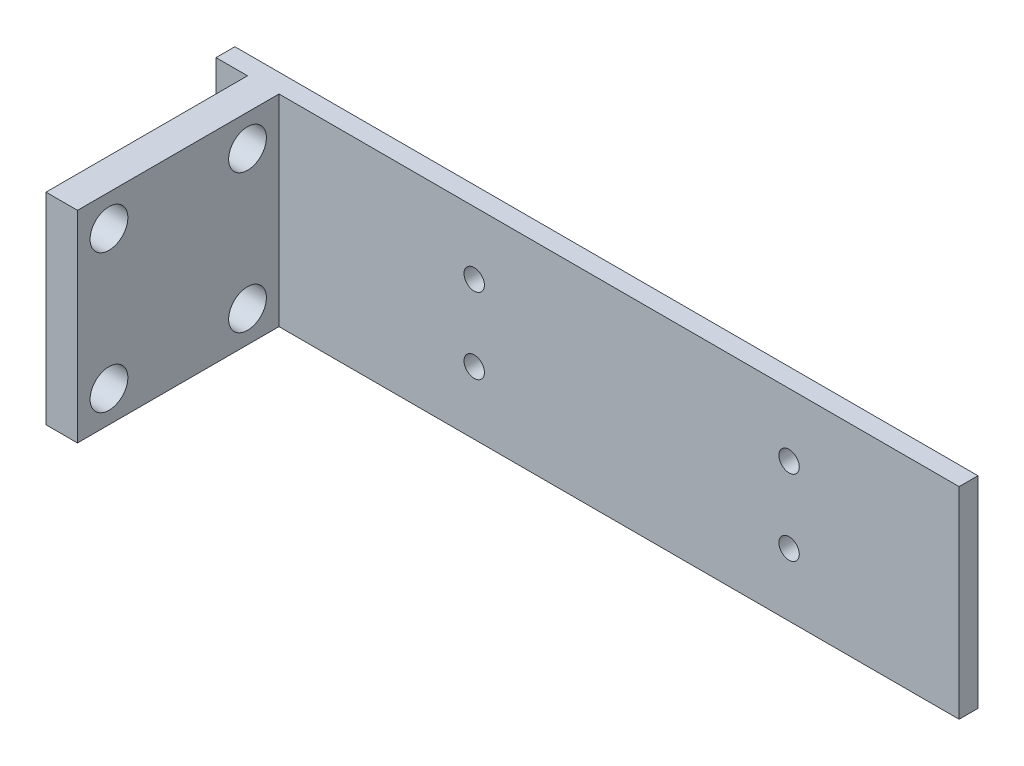
SolidWorks part; units mm, degrees
ref_plane "前视基准面" through (0, 0, 0) normal (0, 0, 1) x (1, 0, 0)
ref_plane "上视基准面" through (0, 0, 0) normal (0, 1, 0) x (1, 0, 0)
ref_plane "右视基准面" through (0, 0, 0) normal (1, 0, 0) x (0, 0, -1)
sketch "草图1" plane through (0, 0, 0) normal (0, 0, 1) x (1, 0, 0)
  line L1 (-71.2816, 22.717) -> (46.7184, 22.717)
  line L2 (-71.2816, 22.717) -> (-71.2816, -9.283)
  line L3 (-71.2816, -9.283) -> (46.7184, -9.283)
  line L4 (46.7184, 22.717) -> (46.7184, -9.283)
  dimension "D1" = 118
  dimension "D2" = 32
extrude "凸台-拉伸1" add sketch "草图1" along normal blind 3
sketch "草图2" plane through (0, 0, 3) normal (0, 0, 1) x (1, 0, 0)
  line L0 (-71.2816, 22.717) -> (-71.2816, -9.283) construction
  line L1 (46.7184, 22.717) -> (-71.2816, 22.717) construction
  line L2 (-71.2816, -9.283) -> (46.7184, -9.283) construction
  circle A0 centre (-30.2816, 12.717) radius 1.62
  circle A1 centre (-30.2816, 0.717) radius 1.62
  circle A2 centre (19.7184, 12.717) radius 1.62
  circle A3 centre (19.7184, 0.717) radius 1.62
  dimension "D1" = 3.24
  dimension "D2" = 41
  dimension "D3" = 10
  dimension "D4" = 3.24
  dimension "D5" = 10
  dimension "D6" = 41
  dimension "D7" = 3.24
  dimension "D8" = 50
  dimension "D9" = 3.24
extrude "切除-拉伸1" cut sketch "草图2" against normal blind 3
sketch "草图3" plane through (0, 0, 3) normal (0, 0, 1) x (1, 0, 0)
  line L0 (-71.2816, -9.283) -> (46.7184, -9.283) construction
  line L1 (-66.2816, 22.717) -> (-61.2816, 22.717)
  line L2 (-66.2816, 22.717) -> (-66.2816, -9.283)
  line L3 (-66.2816, -9.283) -> (-61.2816, -9.283)
  line L4 (-61.2816, 22.717) -> (-61.2816, -9.283)
  line L5 (-71.2816, 22.717) -> (-71.2816, -9.283) construction
  dimension "D1" = 5
  dimension "D2" = 5
extrude "凸台-拉伸2" add sketch "草图3" along normal blind 32
sketch "草图4" plane through (-71.2816, 0, 0) normal (-1, 0, 0) x (0, 0, 1)
  line L0 (35, 22.717) -> (35, -9.283) construction
  line L1 (3, 22.717) -> (0, 22.717) construction
  line L2 (3, -9.283) -> (0, -9.283) construction
  line L3 (0, 22.717) -> (0, -9.283) construction
  circle A0 centre (30, 17.717) radius 3
  circle A1 centre (30, -4.283) radius 3
  circle A2 centre (8, 17.717) radius 3
  circle A3 centre (8, -4.283) radius 3
  dimension "D1" = 5
  dimension "D3" = 5
  dimension "D4" = 5
  dimension "D5" = 8
  dimension "D2" = 5
extrude "切除-拉伸2" cut sketch "草图4" against normal blind 32
